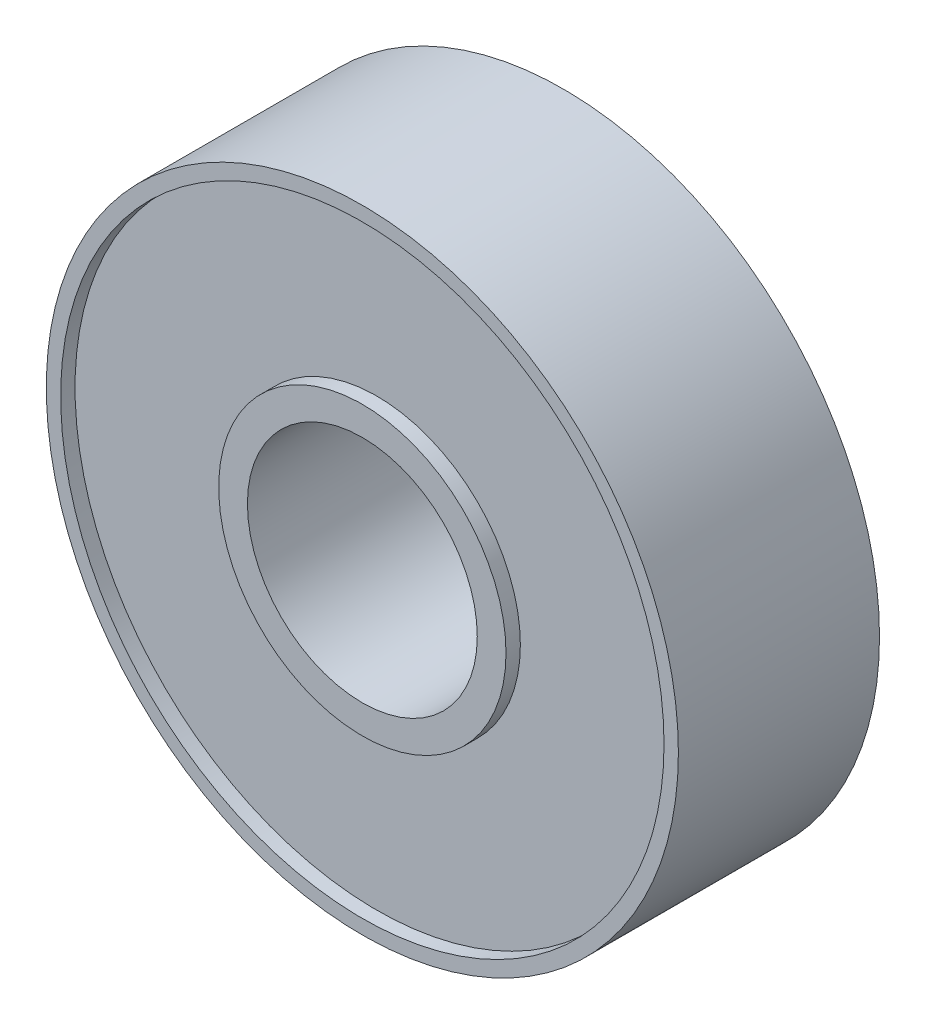
SolidWorks part; units mm, degrees
material "Stainless Steel (ferritic)"
ref_plane "Front Plane" through (0, 0, 0) normal (0, 0, 1) x (1, 0, 0)
ref_plane "Top Plane" through (0, 0, 0) normal (0, 1, 0) x (1, 0, 0)
ref_plane "Right Plane" through (0, 0, 0) normal (1, 0, 0) x (0, 0, -1)
sketch "Sketch1" plane through (0, 0, 0) normal (0, 0, 1) x (1, 0, 0)
  circle A0 centre (0, 0) radius 4
  circle A1 centre (0, 0) radius 11
  dimension "D1" = 8
  dimension "D2" = 22
extrude "Boss-Extrude1" add sketch "Sketch1" along normal mid plane 7
sketch "Sketch2" plane through (0, 0, 3.5) normal (0, 0, 1) x (1, 0, 0)
  circle A0 centre (0, 0) radius 4 construction
  circle A1 centre (0, 0) radius 11
  circle A2 centre (0, 0) radius 11
  circle A3 centre (0, 0) radius 4
  circle A4 centre (0, 0) radius 10.5
  circle A5 centre (0, 0) radius 5
  dimension "D1" = 0
  dimension "D2" = 0.5
  dimension "D3" = 1
extrude "Cut-Extrude1" cut sketch "Sketch2" against normal blind 0.5 contours A4 A5
mirror "Mirror1" about plane through (0, 0, 0) normal (0, 0, 1) of "Cut-Extrude1"
